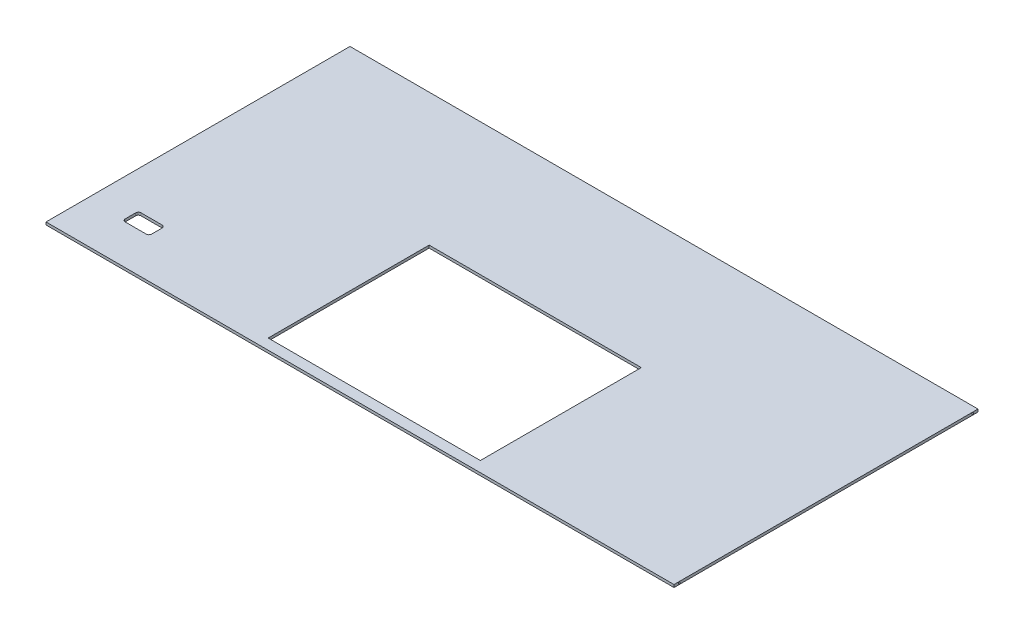
SolidWorks part; units mm, degrees
ref_plane "Front Plane" through (0, 0, 0) normal (0, 0, 1) x (1, 0, 0)
ref_plane "Top Plane" through (0, 0, 0) normal (0, 1, 0) x (1, 0, 0)
ref_plane "Right Plane" through (0, 0, 0) normal (1, 0, 0) x (0, 0, -1)
sketch "Sketch1" plane through (0, 0, 0) normal (0, 1, 0) x (1, 0, 0)
  line L1 (595, -288) -> (-595, -288)
  line L2 (595, -288) -> (595, 288)
  line L3 (595, 288) -> (-595, 288)
  line L4 (-595, -288) -> (-595, 288)
  line L5 (595, -288) -> (-595, 288) construction
  line L6 (595, 288) -> (-595, -288) construction
  point P0 (0, 0)
  dimension "D1" = 576
  dimension "D2" = 1190
extrude "Boss-Extrude1" add sketch "Sketch1" along normal blind 5
sketch "Sketch2" plane through (595, 0, 0) normal (1, 0, 0) x (0, 0, -1)
  line L0 (-288, 5) -> (-288, 0) construction
  line L1 (-288, 2.5) -> (-278, 2.5) construction
  line L2 (0, 0) -> (0, 5) construction
  line L3 (-288, 5) -> (288, 5) construction
  line L4 (288, 2.5) -> (278, 2.5) construction
  circle A0 centre (-278, 2.5) radius 1.5
  circle A1 centre (278, 2.5) radius 1.5
  dimension "D1" = 3
  dimension "D2" = 10
extrude "Cut-Extrude1" cut sketch "Sketch2" against normal blind 10
mirror "Mirror1" about plane through (0, 0, 0) normal (1, 0, 0) of "Cut-Extrude1"
sketch "Sketch3" plane through (0, 5, 0) normal (0, 1, 0) x (1, 0, 0)
  line L1 (-70, -218) -> (80, -218)
  line L2 (-70, -218) -> (-70, -68)
  line L3 (-70, -68) -> (80, -68)
  line L4 (80, -218) -> (80, -68)
  line L5 (-70, -218) -> (80, -68) construction
  line L6 (-70, -68) -> (80, -218) construction
  line L8 (595, -288) -> (595, 288) construction
  line L9 (-600, -278) -> (600, -278) construction
  point P0 (5, -143)
  dimension "D1" = 60
  dimension "D2" = 150
  dimension "D3" = 150
  dimension "D4" = 515
extrude "Cut-Extrude2" cut sketch "Sketch3" against normal blind 10
sketch "Sketch4" plane through (0, 5, 0) normal (0, 1, 0) x (1, 0, 0)
  line L1 (-194, 37) -> (208, 37)
  line L2 (-194, 37) -> (-194, -268)
  line L3 (-194, -268) -> (208, -268)
  line L4 (208, 37) -> (208, -268)
  line L5 (-595, -288) -> (595, -288) construction
  line L6 (595, -288) -> (595, 288) construction
  dimension "D1" = 305
  dimension "D2" = 20
  dimension "D3" = 387
  dimension "D4" = 402
extrude "Cut-Extrude3" cut sketch "Sketch4" against normal blind 6
sketch "Sketch5" plane through (0, 5, 0) normal (0, 1, 0) x (1, 0, 0)
  line L0 (-520, -183) -> (-480, -183)
  line L1 (-475, -188) -> (-475, -208)
  line L2 (-480, -213) -> (-520, -213)
  line L3 (-525, -208) -> (-525, -188)
  arc A0 (-520, -183) -> (-525, -188) centre (-520, -188) ccw construction
  arc A1 (-480, -183) -> (-475, -188) centre (-480, -188) cw
  arc A2 (-475, -208) -> (-480, -213) centre (-480, -208) cw
  arc A3 (-520, -213) -> (-525, -208) centre (-520, -208) cw
  arc A4 (-525, -188) -> (-520, -183) centre (-520, -188) cw
extrude "Cut-Extrude4" cut sketch "Sketch5" against normal blind 10
